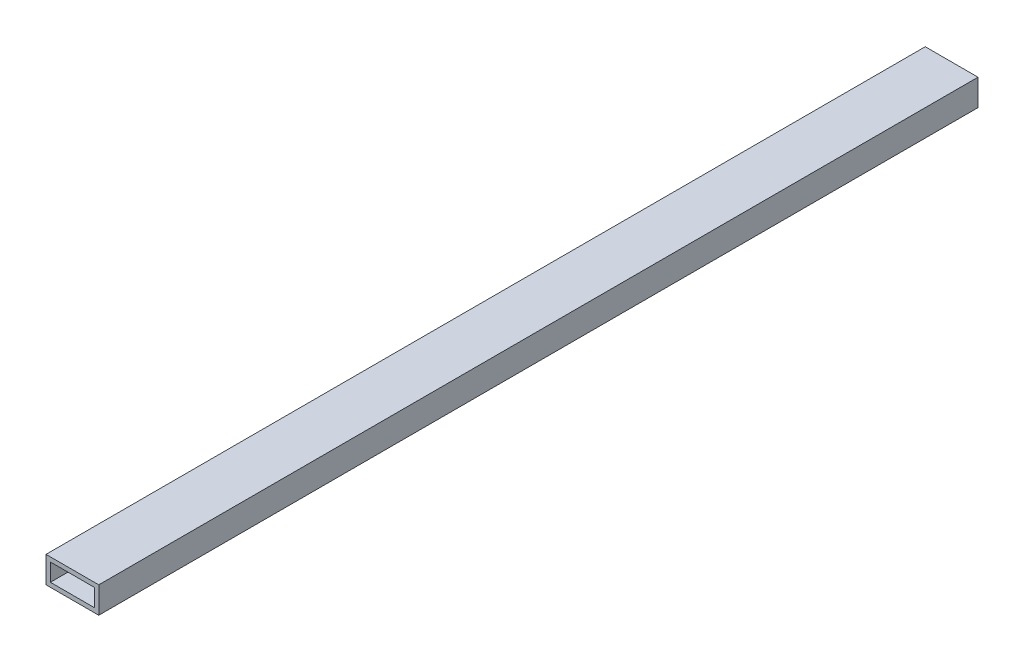
SolidWorks part; units mm, degrees
ref_plane "Front Plane" through (0, 0, 0) normal (0, 0, 1) x (1, 0, 0)
ref_plane "Top Plane" through (0, 0, 0) normal (0, 1, 0) x (1, 0, 0)
ref_plane "Right Plane" through (0, 0, 0) normal (1, 0, 0) x (0, 0, -1)
sketch "Sketch1" plane through (0, 0, 0) normal (0, 0, 1) x (1, 0, 0)
  line L0 (-15.875, 6.35) -> (15.875, 6.35)
  line L2 (-19.05, 9.525) -> (19.05, 9.525)
  line L3 (-19.05, 9.525) -> (-19.05, -9.525)
  line L4 (-19.05, -9.525) -> (19.05, -9.525)
  line L5 (19.05, 9.525) -> (19.05, -9.525)
  line L10 (15.875, 6.35) -> (15.875, -6.35)
  line L11 (-15.875, -6.35) -> (15.875, -6.35)
  line L12 (-15.875, 6.35) -> (-15.875, -6.35)
  point P12 (0, 9.525)
  point P14 (19.05, 0)
  dimension "Wall Thickness" = 3.175
  dimension "Outside Width" = 38.1
  dimension "Outside Height" = 19.05
  dimension "Inside Height" = 12.7
  dimension "Inside Width" = 31.75
sketch "Sketch2" plane through (0, 0, 0) normal (1, 0, 0) x (0, 0, -1)
  line L0 (317.5, 0) -> (-317.5, 0)
  point P4 (0, 0)
  point P7 (-317.5, 0)
  point P10 (317.5, 0)
  dimension "Length" = 635
sketch "Sketch3" plane through (0, 0, 0) normal (0, 0, 1) x (1, 0, 0)
  line L21 (19.05, 9.525) -> (-19.05, 9.525)
  line L22 (19.05, -9.525) -> (19.05, 9.525)
  line L23 (-19.05, -9.525) -> (19.05, -9.525)
  line L24 (-19.05, 9.525) -> (-19.05, -9.525)
  line L25 (19.05, 9.525) -> (-19.05, 9.525)
  line L26 (19.05, -9.525) -> (19.05, 9.525)
  line L27 (-19.05, -9.525) -> (19.05, -9.525)
  line L28 (-19.05, 9.525) -> (-19.05, -9.525)
  line L29 (15.875, 6.35) -> (-15.875, 6.35)
  line L30 (15.875, -6.35) -> (15.875, 6.35)
  line L31 (-15.875, -6.35) -> (15.875, -6.35)
  line L32 (-15.875, 6.35) -> (-15.875, -6.35)
  line L33 (15.875, 6.35) -> (-15.875, 6.35)
  line L34 (15.875, -6.35) -> (15.875, 6.35)
  line L35 (-15.875, -6.35) -> (15.875, -6.35)
  line L36 (-15.875, 6.35) -> (-15.875, -6.35)
  dimension "D1" = 0
  dimension "D2" = 0
extrude "Boss-Extrude1" add sketch "Sketch3" along normal up to vertex (317.5 mm away) and the other way up to vertex (317.5 mm away) up to point (0, 0, 317.5) other way up to point (0, 0, -317.5)
sketch "Drawing Reference" plane through (0, 0, 0) normal (1, 0, 0) x (0, 0, -1)
  line L0 (-317.5, 0) -> (317.5, 0) construction
  line L1 (0, -9.525) -> (0, 9.525) construction
  line L2 (-317.5, -9.525) -> (317.5, -9.525) construction
  line L5 (-317.5, 9.525) -> (317.5, 9.525) construction
  point P7 (-290.068, 0)
  point P8 (290.068, 0)
  dimension "D1" = 27.432
equation "\"D1@Drawing Reference\"=\"Outside Width@Sketch1\" * 0.72"
